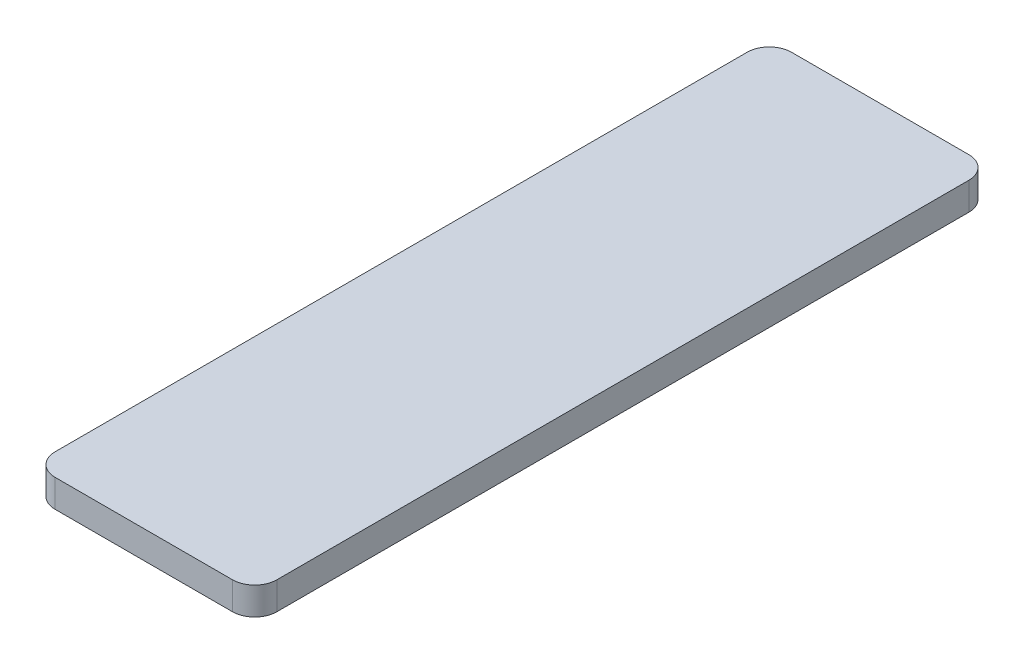
SolidWorks part; units mm, degrees
material "Acrylic (Medium-high impact)"
ref_plane "Front Plane" through (0, 0, 0) normal (0, 0, 1) x (1, 0, 0)
ref_plane "Top Plane" through (0, 0, 0) normal (0, 1, 0) x (1, 0, 0)
ref_plane "Right Plane" through (0, 0, 0) normal (1, 0, 0) x (0, 0, -1)
ref_plane "Plane1" through (0, 0, 0) normal (0, 1, 0) x (1, 0, 0)
sketch "Sketch1" plane through (0, 0, 0) normal (0, 1, 0) x (1, 0, 0)
  line L1 (0, 0) -> (25.4, 0)
  line L2 (0, 0) -> (0, 84.35)
  line L3 (0, 84.35) -> (25.4, 84.35)
  line L4 (25.4, 0) -> (25.4, 84.35)
  dimension "D1" = 25.4
  dimension "D2" = 84.35
extrude "Boss-Extrude1" add sketch "Sketch1" along normal blind 3.175
fillet "Fillet1" radius 2.54 4 edges at (25.4, 1.5875, 0) (0, 1.5875, 0) (25.4, 1.5875, -84.35) (0, 1.5875, -84.35)
